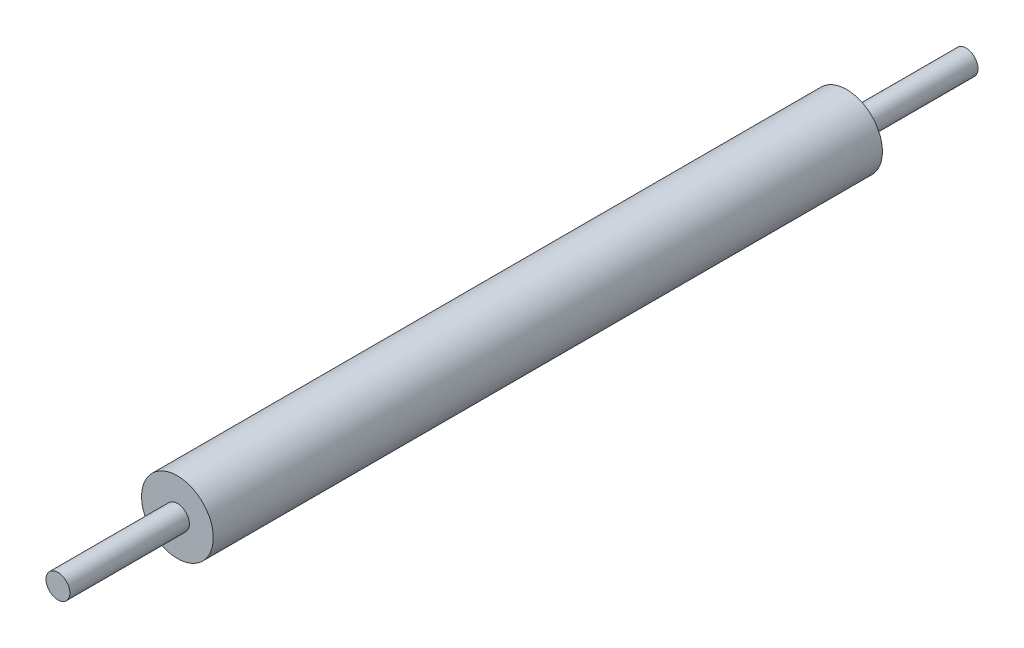
SolidWorks part; units mm, degrees
ref_plane "Front Plane" through (0, 0, 0) normal (0, 0, 1) x (1, 0, 0)
ref_plane "Top Plane" through (0, 0, 0) normal (0, 1, 0) x (1, 0, 0)
ref_plane "Right Plane" through (0, 0, 0) normal (1, 0, 0) x (0, 0, -1)
sketch "Sketch1" plane through (0, 0, 0) normal (0, 0, 1) x (1, 0, 0)
  circle A0 centre (0, 0) radius 38.1
  dimension "D1" = 76.2
extrude "Boss-Extrude5" add sketch "Sketch1" along normal blind 711.2
sketch "Sketch3" plane through (0, 0, 711.2) normal (0, 0, 1) x (1, 0, 0)
  circle A0 centre (0, 0) radius 12.7
  dimension "D1" = 25.4
extrude "Boss-Extrude8" add sketch "Sketch3" along normal blind 127
sketch "Sketch4" plane through (0, 0, 0) normal (0, 0, -1) x (-1, 0, 0)
  circle A0 centre (0, 0) radius 12.7
  dimension "D1" = 25.4
extrude "Boss-Extrude9" add sketch "Sketch4" along normal blind 127
